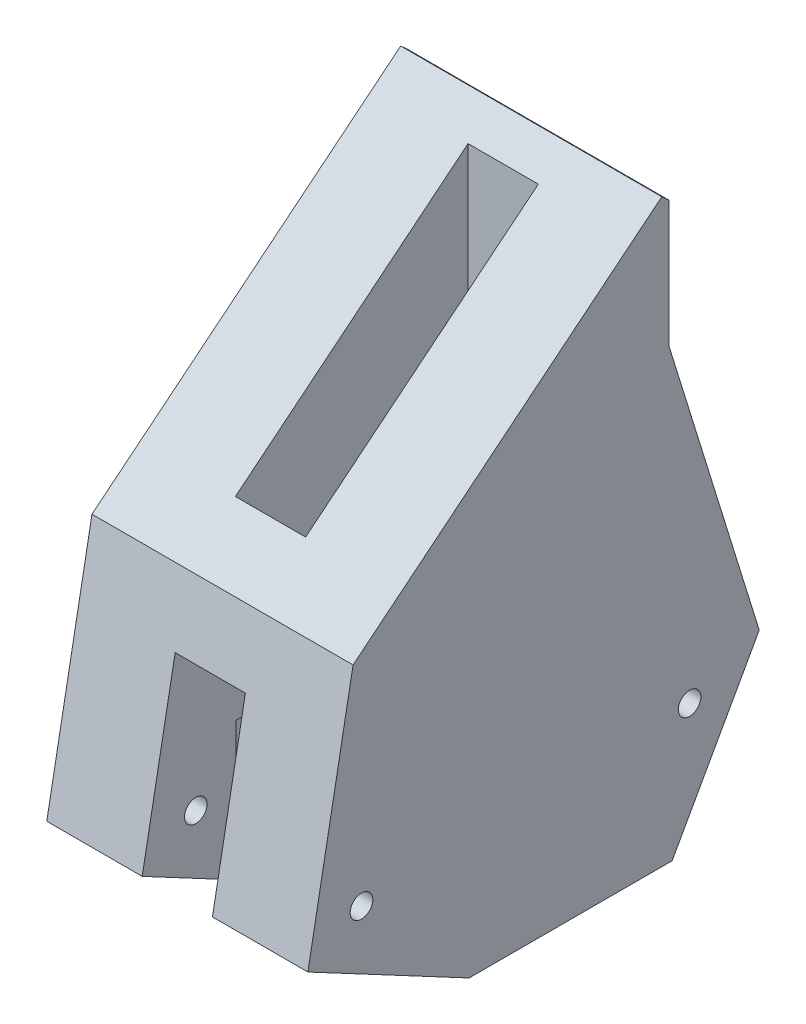
SolidWorks part; units mm, degrees
ref_plane "정면" through (0, 0, 0) normal (0, 0, 1) x (1, 0, 0)
ref_plane "윗면" through (0, 0, 0) normal (0, 1, 0) x (1, 0, 0)
ref_plane "우측면" through (0, 0, 0) normal (1, 0, 0) x (0, 0, -1)
sketch "스케치1" plane through (0, 0, 0) normal (1, 0, 0) x (0, 0, -1)
  line L0 (0, 0) -> (34.9906, 0)
  line L1 (34.9906, 0) -> (50, 26.9231)
  line L2 (50, 26.9231) -> (34.4757, 76.9954)
  line L3 (34.4757, 76.9954) -> (34.4757, 98.8423)
  line L4 (33.2056, 100) -> (-19.9959, 56.7214)
  line L5 (-19.9959, 56.7214) -> (-27.7853, 14.7832)
  line L6 (-27.7853, 14.7832) -> (0, 0)
  line L7 (34.4757, 98.8423) -> (33.2056, 100)
  dimension "D1" = 50
  dimension "D2" = 100
extrude "보스-돌출1" add sketch "스케치1" along normal mid plane 45
sketch "스케치2" plane through (0, 0, 0) normal (1, 0, 0) x (0, 0, -1)
  line L1 (-11.7234, 116.7473) -> (28.3766, 116.7473)
  line L2 (-11.7234, 116.7473) -> (-11.7234, -18.2015)
  line L3 (-11.7234, -18.2015) -> (28.3766, -18.2015)
  line L4 (28.3766, 116.7473) -> (28.3766, -18.2015)
  dimension "D1" = 40.1
extrude "컷-돌출1" cut sketch "스케치2" against normal mid plane 12.1
sketch "스케치3" plane through (0, 0, 0) normal (1, 0, 0) x (0, 0, -1)
  line L1 (-11.6234, 30) -> (28.3766, 30)
  line L2 (-11.6234, 30) -> (-11.6234, -24.5321)
  line L3 (-11.6234, -24.5321) -> (28.3766, -24.5321)
  line L4 (28.3766, 30) -> (28.3766, -24.5321)
  line L5 (28.3766, 0) -> (28.3766, 96.0717) construction
  dimension "D1" = 40
  dimension "D2" = 30
extrude "컷-돌출2" cut sketch "스케치3" against normal mid plane 34
sketch "스케치4" plane through (0, 0, 0) normal (1, 0, 0) x (0, 0, -1)
  circle A0 centre (-18.5464, 20) radius 1.95
  circle A1 centre (38, 22) radius 1.95
  dimension "D1" = 3.9
  dimension "D2" = 3.9
  dimension "D3" = 20
  dimension "D4" = 22
  dimension "D5" = 38
extrude "컷-돌출3" cut sketch "스케치4" against normal through all both and the other way through all
sketch "스케치5" plane through (0, 0, 0) normal (1, 0, 0) x (0, 0, -1)
  line L1 (-36.9382, 45.3447) -> (-8.0433, 45.3447)
  line L2 (-36.9382, 45.3447) -> (-36.9382, -14.9691)
  line L3 (-36.9382, -14.9691) -> (-8.0433, -14.9691)
  line L4 (-8.0433, 45.3447) -> (-8.0433, -14.9691)
  line L5 (59.7104, 40.1712) -> (23.6747, 40.1712)
  line L6 (59.7104, 40.1712) -> (59.7104, -13.6406)
  line L7 (59.7104, -13.6406) -> (23.6747, -13.6406)
  line L8 (23.6747, 40.1712) -> (23.6747, -13.6406)
extrude "컷-돌출4" cut sketch "스케치5" against normal mid plane 12.1
